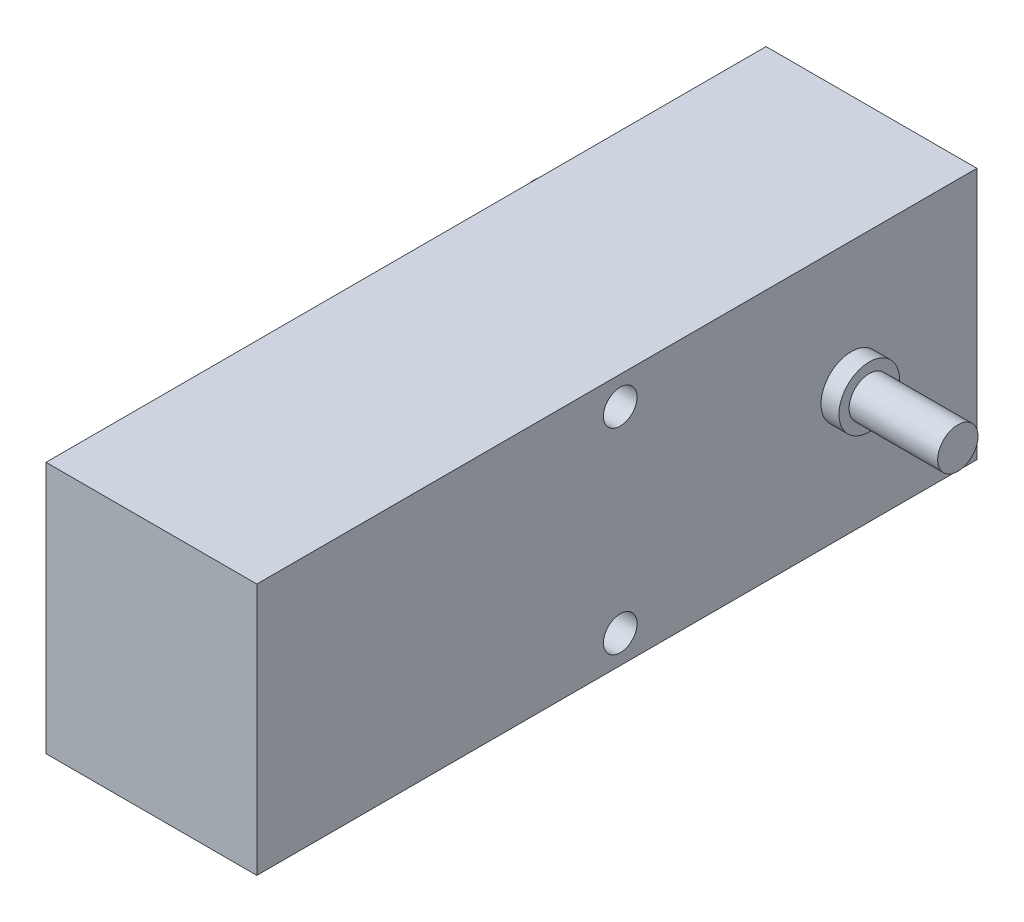
SolidWorks part; units mm, degrees
ref_plane "Front Plane" through (0, 0, 0) normal (0, 0, 1) x (1, 0, 0)
ref_plane "Top Plane" through (0, 0, 0) normal (0, 1, 0) x (1, 0, 0)
ref_plane "Right Plane" through (0, 0, 0) normal (1, 0, 0) x (0, 0, -1)
sketch "Sketch1" plane through (0, 0, 0) normal (1, 0, 0) x (0, 0, -1)
  line L1 (-32.1, 11.25) -> (32.1, 11.25)
  line L2 (-32.1, 11.25) -> (-32.1, -11.25)
  line L3 (-32.1, -11.25) -> (32.1, -11.25)
  line L4 (32.1, 11.25) -> (32.1, -11.25)
  line L5 (-32.1, 11.25) -> (32.1, -11.25) construction
  line L6 (-32.1, -11.25) -> (32.1, 11.25) construction
  point P0 (0, 0)
  dimension "D1" = 64.2
  dimension "D2" = 22.5
extrude "Boss-Extrude1" add sketch "Sketch1" along normal mid plane 18.8
sketch "Sketch2" plane through (0, 0, 0) normal (0, 1, 0) x (1, 0, 0)
  line L0 (0, 0) -> (0, 32.1) construction
  line L1 (9.4, 32.1) -> (-9.4, 32.1) construction
  line L2 (0, 20.9) -> (18.9, 20.9) construction
  line L3 (18.9, 20.9) -> (18.9, 22.7)
  line L4 (18.9, 22.7) -> (11, 22.7)
  line L5 (11, 22.7) -> (11, 23.6)
  line L6 (11, 23.6) -> (9.4, 23.6)
  line L7 (9.4, 32.1) -> (9.4, -32.1) construction
  line L8 (9.4, 23.6) -> (9.4, 20.9)
  line L9 (9.4, 20.9) -> (18.9, 20.9)
  line L10 (-9.4, 23.6) -> (-9.4, 20.9)
  line L11 (-11, 23.6) -> (-9.4, 23.6)
  line L12 (-11, 22.7) -> (-11, 23.6)
  line L13 (-18.9, 22.7) -> (-11, 22.7)
  line L14 (-18.9, 20.9) -> (-18.9, 22.7)
  line L15 (-9.4, 20.9) -> (-18.9, 20.9)
  dimension "D1" = 9.5
  dimension "D2" = 7.9
  dimension "D3" = 3.6
  dimension "D4" = 5.4
  dimension "D5" = 11.2
revolve "Revolve1" add sketch "Sketch2" angle 360 about L2
sketch "Sketch3" plane through (0, 0, 0) normal (1, 0, 0) x (0, 0, -1)
  line L0 (0, 0) -> (34.6, 0) construction
  line L1 (32.1, -11.25) -> (32.1, 11.25) construction
  line L2 (37.1, -2.5) -> (32.1, -2.5)
  line L3 (37.1, -2.5) -> (37.1, 2.5)
  line L4 (37.1, 2.5) -> (32.1, 2.5)
  line L5 (32.1, -2.5) -> (32.1, 2.5)
  line L6 (37.1, -2.5) -> (32.1, 2.5) construction
  line L7 (37.1, 2.5) -> (32.1, -2.5) construction
  circle A0 centre (34.7, 0) radius 1.4
  point P7 (34.7, 0)
  point P12 (34.7, -0.0425)
  dimension "D2" = 2.8
  dimension "D1" = 5
  dimension "D3" = 2.4
  dimension "D4" = 5
extrude "Boss-Extrude2" add sketch "Sketch3" along normal mid plane 5
sketch "Sketch4" plane through (0, 0, 0) normal (1, 0, 0) x (0, 0, -1)
  line L0 (0, 0) -> (37.1, 0) construction
  line L2 (32.1, -11.25) -> (32.1, 11.25) construction
  line L3 (37.1, -2.5) -> (37.1, 2.5) construction
  circle A0 centre (0.3, 8.75) radius 1.5
  circle A1 centre (0.3, -8.75) radius 1.5
  dimension "D1" = 31.8
  dimension "D2" = 17.5
  dimension "D3" = 3
extrude "Cut-Extrude1" cut sketch "Sketch4" along normal through all both and the other way through all
